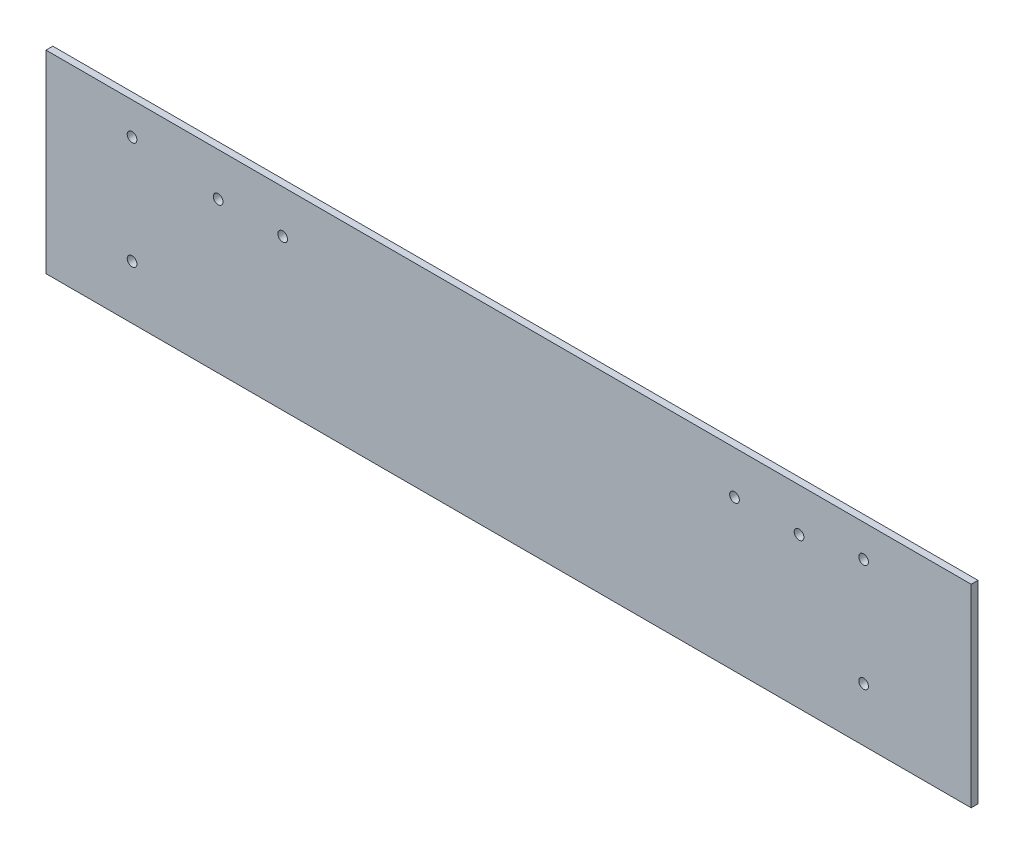
SolidWorks part; units mm, degrees
ref_plane "Front Plane" through (0, 0, 0) normal (0, 0, 1) x (1, 0, 0)
ref_plane "Top Plane" through (0, 0, 0) normal (0, 1, 0) x (1, 0, 0)
ref_plane "Right Plane" through (0, 0, 0) normal (1, 0, 0) x (0, 0, -1)
sketch "Sketch1" plane through (0, 0, 0) normal (0, 0, 1) x (1, 0, 0)
  line L1 (-215, -45) -> (215, -45)
  line L2 (-215, -45) -> (-215, 45)
  line L3 (-215, 45) -> (215, 45)
  line L4 (215, -45) -> (215, 45)
  line L5 (-215, -45) -> (215, 45) construction
  line L6 (-215, 45) -> (215, -45) construction
  point P0 (0, 0)
  dimension "D1" = 430
  dimension "D2" = 90
extrude "Boss-Extrude1" add sketch "Sketch1" along normal blind 3.175
hole_wizard "M4 Clearance Hole1" positions "Sketch2" profile "Sketch3" hole size "M4" standard "ANSI Metric" end condition through all
sketch "Sketch2" plane through (0, 0, 3.175) normal (0, 0, 1) x (1, 0, 0)
  line L1 (-175, -20) -> (165, -20)
  line L2 (-175, -20) -> (-175, 30)
  line L3 (-175, 30) -> (165, 30)
  line L4 (165, -20) -> (165, 30)
  line L5 (-175, -20) -> (165, 30) construction
  line L6 (-175, 30) -> (165, -20) construction
  line L7 (-215, 45) -> (-215, -45) construction
  line L8 (215, -45) -> (215, 45) construction
  line L9 (-215, -45) -> (215, -45) construction
  point P2 (165, 30)
  point P59 (-175, -20)
  point P60 (-175, 30)
  point P61 (165, -20)
  dimension "D1" = 50
  dimension "D2" = 40
  dimension "D3" = 50
  dimension "D4" = 25
sketch "Sketch3" plane through (165, 30, 3.175) normal (1, 0, 0) x (0, -1, 0)
  line L0 (0, 0) -> (0, 3.175)
  line L1 (0, 3.175) -> (2.25, 3.175)
  line L2 (2.25, 3.175) -> (2.25, 0)
  line L5 (2.25, 0) -> (0, 0)
  line L11 (0, -6.35) -> (0, 107.95) construction
  dimension "Thru Hole Dia." = 4.5
  dimension "Thru Hole Depth" = 3.175
hole_wizard "M4 Clearance Hole2" positions "Sketch4" profile "Sketch5" hole size "M4" standard "ANSI Metric" end condition through all
sketch "Sketch4" plane through (0, 0, 3.175) normal (0, 0, 1) x (1, 0, 0)
  line L0 (-135, 25) -> (-105, 25)
  line L1 (215, 45) -> (-215, 45) construction
  line L2 (-215, 45) -> (-215, -45) construction
  point P1 (-135, 25)
  point P2 (-105, 25)
  dimension "D1" = 30
  dimension "D2" = 20
  dimension "D3" = 80
sketch "Sketch5" plane through (-135, 25, 3.175) normal (1, 0, 0) x (0, -1, 0)
  line L0 (0, 0) -> (0, 3.175)
  line L1 (0, 3.175) -> (2.25, 3.175)
  line L2 (2.25, 3.175) -> (2.25, 0)
  line L5 (2.25, 0) -> (0, 0)
  line L11 (0, -6.35) -> (0, 107.95) construction
  dimension "Thru Hole Dia." = 4.5
  dimension "Thru Hole Depth" = 3.175
mirror "Mirror1" about plane through (0, 0, 0) normal (1, 0, 0) of "M4 Clearance Hole2"
